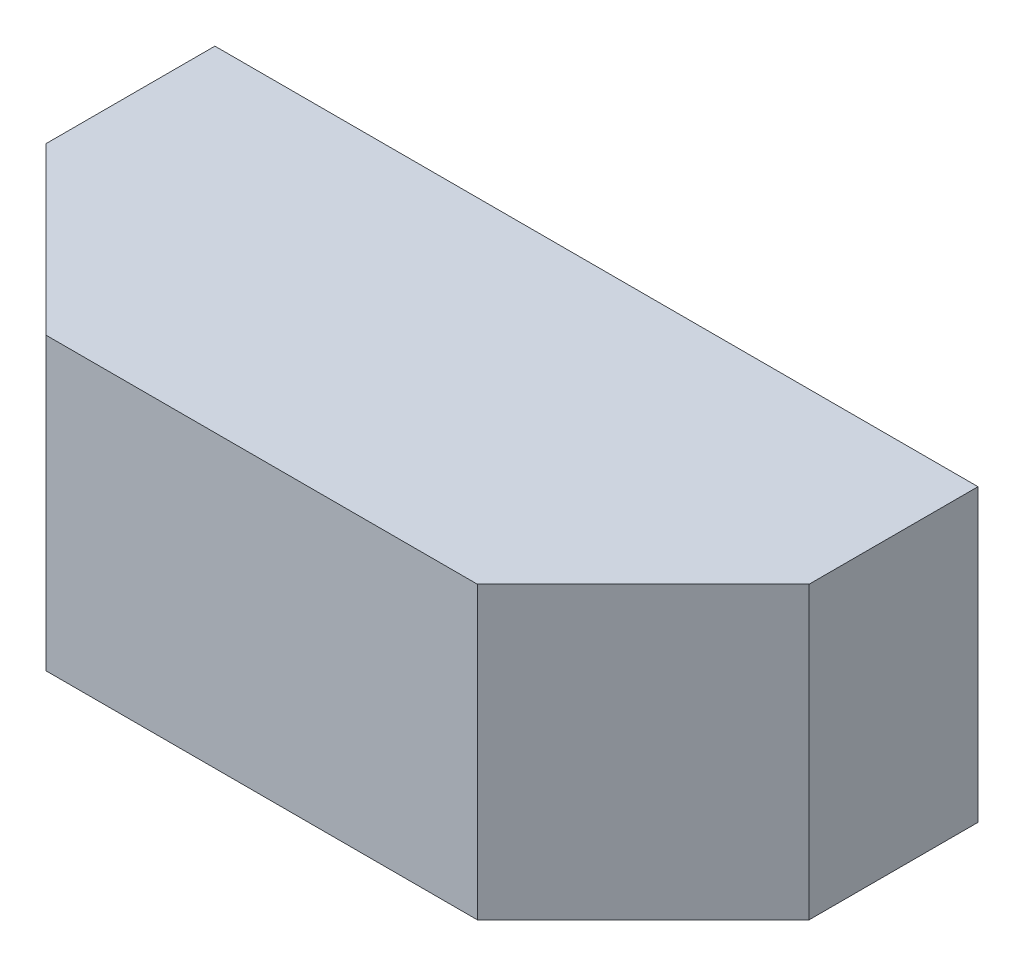
SolidWorks part; units mm, degrees
ref_plane "Plano frontal" through (0, 0, 0) normal (0, 0, 1) x (1, 0, 0)
ref_plane "Plano superior" through (0, 0, 0) normal (0, 1, 0) x (1, 0, 0)
ref_plane "Plano direito" through (0, 0, 0) normal (1, 0, 0) x (0, 0, -1)
sketch "Esboço1" plane through (0, 0, 0) normal (0, 1, 0) x (1, 0, 0)
  line L0 (20.8734, 0) -> (26.67, 5.8)
  line L1 (5.8, 0) -> (20.8734, 0)
  line L2 (0, 5.7966) -> (0, 11.7)
  line L3 (0, 11.7) -> (26.67, 11.7)
  line L4 (26.67, 5.8) -> (26.67, 11.7)
  line L5 (5.8, 0) -> (0, 5.7966)
  dimension "D1" = 26.67
extrude "Ressalto-extrusão1" add sketch "Esboço1" along normal blind 10.16
